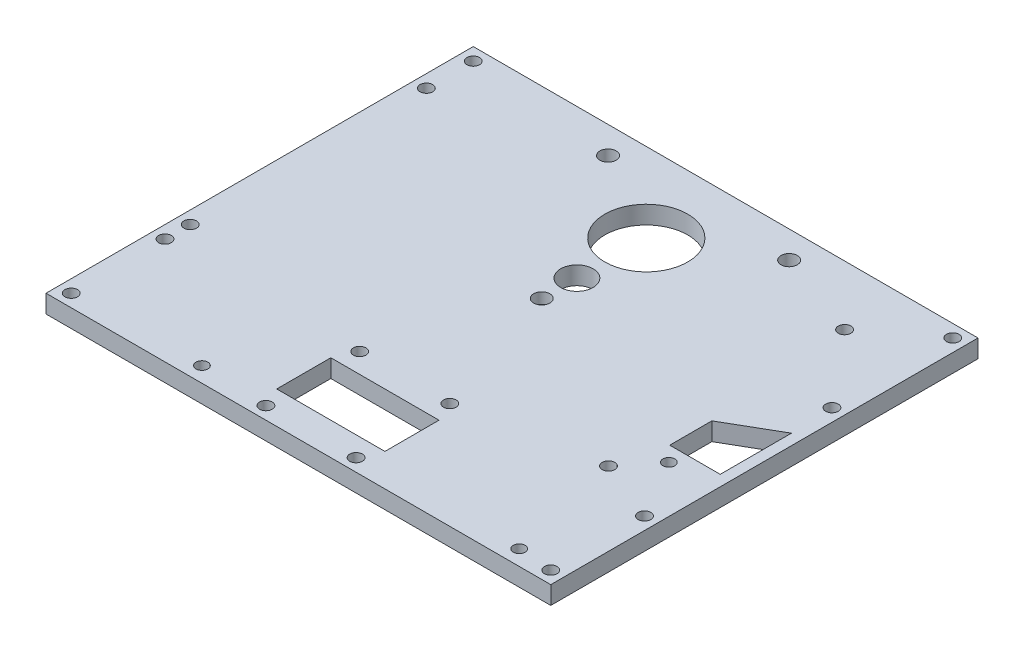
SolidWorks part; units mm, degrees
ref_plane "前视基准面" through (0, 0, 0) normal (0, 0, 1) x (1, 0, 0)
ref_plane "上视基准面" through (0, 0, 0) normal (0, 1, 0) x (1, 0, 0)
ref_plane "右视基准面" through (0, 0, 0) normal (1, 0, 0) x (0, 0, -1)
sketch "草图1" plane through (0, 0, 0) normal (0, 1, 0) x (1, 0, 0)
  line L1 (-40, 90) -> (40, 90)
  line L2 (-40, 90) -> (-40, -90)
  line L3 (-40, -90) -> (40, -90)
  line L4 (40, 90) -> (40, -90)
  line L5 (-40, 90) -> (40, -90) construction
  line L6 (-40, -90) -> (40, 90) construction
  point P0 (0, 0)
  dimension "D1" = 80
  dimension "D2" = 180
extrude "凸台-拉伸1" add sketch "草图1" along normal blind 5
sketch "草图5" plane through (0, 5, 0) normal (0, 1, 0) x (1, 0, 0)
  line L0 (40, -90) -> (40, 90) construction
  line L1 (-40, -90) -> (40, -90) construction
  line L2 (-40, -90) -> (-40, -10) construction
  line L3 (-40, -10) -> (40, -10) construction
  line L4 (40, -90) -> (40, -10) construction
  line L5 (-40, -10) -> (40, -90) construction
  line L6 (0, -50) -> (0, -79)
  line L7 (0, -50) -> (-25.1147, -35.5)
  line L8 (0, -50) -> (25.1147, -35.5)
  circle A0 centre (0, -50) radius 29
  circle A1 centre (0, -50) radius 19.25
  dimension "D2" = 58
  dimension "D5" = 38.5
  dimension "D1" = 80
  dimension "D3" = 120
  dimension "D4" = 120
sketch "草图6" plane through (0, 5, 0) normal (0, 1, 0) x (1, 0, 0)
  point P0 (0, -79)
  point P3 (25.1147, -35.5)
  point P6 (-25.1147, -35.5)
hole_wizard "孔2" positions "草图6" profile "草图7" legacy end condition through all
sketch "草图7" plane through (0, 5, 79) normal (1, 0, 0) x (0, 0, 1)
  line L0 (0, 0) -> (0, 5)
  line L1 (0, 5) -> (2.25, 5)
  line L2 (2.25, 5) -> (2.25, 0)
  line L3 (2.25, 0) -> (0, 0)
  line L4 (0, 110) -> (0, -10) construction
  dimension "直径" = 4.5
  dimension "深度" = 5
sketch "草图8" plane through (0, 5, 0) normal (0, 1, 0) x (1, 0, 0)
  point P0 (0, -50)
hole_wizard "孔3" positions "草图8" profile "草图9" legacy end condition through all
sketch "草图9" plane through (0, 5, 50) normal (1, 0, 0) x (0, 0, 1)
  line L0 (0, 0) -> (0, 5)
  line L1 (0, 5) -> (11.5, 5)
  line L2 (11.5, 5) -> (11.5, 0)
  line L3 (11.5, 0) -> (0, 0)
  line L4 (0, 110) -> (0, -10) construction
  dimension "直径" = 23
  dimension "深度" = 5
sketch "草图10" plane through (0, 5, 0) normal (0, 1, 0) x (1, 0, 0)
  line L0 (0, -50) -> (0, -79) construction
  circle A0 centre (0, -50) radius 19.25 construction
  point P0 (0, -69.25)
hole_wizard "孔4" positions "草图10" profile "草图11" legacy end condition through all
sketch "草图11" plane through (0, 5, 69.25) normal (1, 0, 0) x (0, 0, 1)
  line L0 (0, 0) -> (0, 5)
  line L1 (0, 5) -> (4.5, 5)
  line L2 (4.5, 5) -> (4.5, 0)
  line L3 (4.5, 0) -> (0, 0)
  line L4 (0, 110) -> (0, -10) construction
  dimension "直径" = 9
  dimension "深度" = 5
sketch "草图12" plane through (0, 5, 0) normal (0, 1, 0) x (1, 0, 0)
  line L0 (40, -90) -> (40, 90) construction
  line L1 (-40, -90) -> (40, -90)
  line L2 (-40, -90) -> (-40, -20)
  line L3 (-40, -20) -> (40, -20)
  line L4 (40, -90) -> (40, -20)
  line L6 (-40, -20) -> (40, -20)
  line L7 (-40, -20) -> (-40, 90)
  line L8 (-40, 90) -> (40, 90)
  line L9 (40, -20) -> (40, 90)
  line M7 (40, -90) -> (40, 90)
  line M8 (40, 90) -> (-40, 90)
  line M9 (-40, 90) -> (-40, -90)
  dimension "D1" = 70
extrude "切除-拉伸1" cut sketch "草图12" against normal blind 10 contours L3 M9 M7 M8
sketch "草图13" plane through (0, 5, 0) normal (0, 1, 0) x (1, 0, 0)
  line L1 (-40, -90) -> (40, -90)
  line L2 (-40, -90) -> (-40, -150)
  line L3 (-40, -150) -> (40, -150)
  line L4 (40, -90) -> (40, -150)
  dimension "D1" = 60
extrude "凸台-拉伸2" add sketch "草图13" against normal blind 5
sketch "草图14" plane through (0, 5, 0) normal (0, 1, 0) x (1, 0, 0)
  line L0 (-40, -150) -> (40, -150) construction
  line L1 (-40, -20) -> (-70, -20)
  line L2 (-40, -20) -> (-40, -150)
  line L3 (-40, -150) -> (-70, -150)
  line L4 (-70, -20) -> (-70, -150)
  line L5 (40, -20) -> (70, -20)
  line L6 (40, -20) -> (40, -150)
  line L7 (40, -150) -> (70, -150)
  line L8 (70, -20) -> (70, -150)
  dimension "D1" = 30
  dimension "D2" = 30
extrude "凸台-拉伸3" add sketch "草图14" against normal blind 5
sketch "草图15" plane through (0, 5, 0) normal (0, 1, 0) x (1, 0, 0)
  line L0 (70, -150) -> (70, -20) construction
  line L1 (-70, -20) -> (70, -20)
  line L2 (-70, -20) -> (-70, -28)
  line L3 (-70, -28) -> (70, -28)
  line L4 (70, -20) -> (70, -28)
  dimension "D1" = 8
extrude "切除-拉伸2" cut sketch "草图15" against normal blind 10
sketch "草图16" plane through (0, 5, 0) normal (0, 1, 0) x (1, 0, 0)
  line L0 (70, -150) -> (70, -28) construction
  line L1 (-70, -150) -> (70, -150)
  line L2 (-70, -150) -> (-70, -168)
  line L3 (-70, -168) -> (70, -168)
  line L4 (70, -150) -> (70, -168)
  dimension "D1" = 18
extrude "凸台-拉伸4" add sketch "草图16" against normal blind 5
sketch "草图18" plane through (0, 0, 0) normal (0, -1, 0) x (-1, 0, 0)
  point P0 (0, -79)
hole_wizard "孔5" positions "草图18" profile "草图19" legacy
sketch "草图19" plane through (0, 0, 79) normal (1, 0, 0) x (0, 0, -1)
  line L0 (0, 0) -> (0, 2)
  line L1 (0, 2) -> (4.5, 2)
  line L2 (4.5, 2) -> (4.5, 0)
  line L3 (4.5, 0) -> (0, 0)
  line L4 (0, 110) -> (0, -10) construction
  dimension "直径" = 9
  dimension "深度" = 2
sketch "草图20" plane through (0, 0, 0) normal (0, -1, 0) x (-1, 0, 0)
  line L0 (70, -113.5) -> (-70, -113.5)
  line L1 (70, -28) -> (70, -168) construction
  line L2 (-70, -168) -> (-70, -28) construction
  line L3 (70, -28) -> (-70, -28) construction
  line L4 (70, -41) -> (-70, -41)
  line L5 (70, -41) -> (-53, -113.5)
  line L6 (70, -113.5) -> (-70, -113.5)
  line L7 (70, -113.5) -> (70, -41)
  line L8 (70, -41) -> (-70, -41)
  line L9 (-70, -113.5) -> (-70, -41)
  line L10 (70, -113.5) -> (-53, -113.5)
  line L11 (70, -113.5) -> (70, -41)
  line L12 (70, -41) -> (-53, -41)
  line L13 (-53, -113.5) -> (-53, -41)
  line L15 (66.5, -110) -> (-49.5, -110)
  line L16 (66.5, -110) -> (66.5, -44.5)
  line L17 (66.5, -44.5) -> (-49.5, -44.5)
  line L18 (-49.5, -110) -> (-49.5, -44.5)
  line L19 (66.5, -110) -> (-49.5, -44.5) construction
  line L20 (66.5, -44.5) -> (-49.5, -110) construction
  point P12 (8.5, -77.25)
  dimension "D1" = 13
  dimension "D2" = 72.5
  dimension "D3" = 123
  dimension "D4" = 65.5
  dimension "D5" = 116
sketch "草图21" plane through (0, 0, 0) normal (0, -1, 0) x (-1, 0, 0)
  point P0 (-49.5, -44.5)
  point P3 (-49.5, -110)
  point P6 (66.5, -110)
  point P9 (66.5, -44.5)
hole_wizard "孔6" positions "草图21" profile "草图22" legacy end condition through all
sketch "草图22" plane through (49.5, 0, 44.5) normal (1, 0, 0) x (0, 0, -1)
  line L0 (0, 0) -> (0, 5)
  line L1 (0, 5) -> (1.75, 5)
  line L2 (1.75, 5) -> (1.75, 0)
  line L3 (1.75, 0) -> (0, 0)
  line L4 (0, 110) -> (0, -10) construction
  dimension "直径" = 3.5
  dimension "深度" = 5
sketch "草图23" plane through (0, 5, 0) normal (0, 1, 0) x (1, 0, 0)
  line L1 (-70, -113.5) -> (-9, -113.5)
  line L2 (-70, -113.5) -> (-70, -146.5)
  line L3 (-70, -146.5) -> (-9, -146.5)
  line L4 (-9, -113.5) -> (-9, -146.5)
  line L5 (-70, -113.5) -> (70, -113.5) construction
  line L6 (70, -146.5) -> (9, -146.5)
  line L7 (70, -146.5) -> (70, -113.5)
  line L8 (70, -113.5) -> (9, -113.5)
  line L9 (9, -146.5) -> (9, -113.5)
  point P14 (-66.5, -117)
  point P15 (-66.5, -143)
  point P16 (-12.5, -117)
  point P17 (-12.5, -143)
  dimension "D1" = 61
  dimension "D2" = 61
  dimension "D3" = 3.5
  dimension "D4" = 3.5
  dimension "D5" = 3.5
  dimension "D6" = 3.5
  dimension "D7" = 3.5
  dimension "D8" = 3.5
  dimension "D9" = 3.5
  dimension "D10" = 3.5
  dimension "D11" = 33
  dimension "D12" = 33
sketch "草图24" plane through (0, 5, 0) normal (0, 1, 0) x (1, 0, 0)
  point P0 (-66.5, -117)
  point P3 (-12.5, -117)
  point P6 (-12.5, -143)
  point P9 (-66.5, -143)
hole_wizard "孔7" positions "草图24" profile "草图25" legacy end condition through all
sketch "草图25" plane through (-66.5, 5, 117) normal (1, 0, 0) x (0, 0, 1)
  line L0 (0, 0) -> (0, 5)
  line L1 (0, 5) -> (1.75, 5)
  line L2 (1.75, 5) -> (1.75, 0)
  line L3 (1.75, 0) -> (0, 0)
  line L4 (0, 110) -> (0, -10) construction
  dimension "直径" = 3.5
  dimension "深度" = 5
ref_plane "基准面1" through (0, 0, 0) normal (-1, 0, 0) x (0, 0, 1)
mirror "镜向1" about plane through (0, 0, 0) normal (-1, 0, 0) of "孔7"
sketch "草图26" plane through (0, 5, 0) normal (0, 1, 0) x (1, 0, 0)
  line L1 (-70, -168) -> (70, -168)
  line L2 (-70, -168) -> (-70, -146.5)
  line L3 (-70, -146.5) -> (70, -146.5)
  line L4 (70, -168) -> (70, -146.5)
extrude "切除-拉伸3" cut sketch "草图26" against normal blind 10
sketch "草图27" plane through (0, 5, 0) normal (0, 1, 0) x (1, 0, 0)
  line L0 (-70, -28) -> (70, -28) construction
  line L1 (-70, -28) -> (-70, -146.5) construction
  line L2 (70, -146.5) -> (70, -28) construction
  point P0 (-66.5, -31.5)
  point P1 (66.5, -31.5)
  dimension "D1" = 3.5
  dimension "D2" = 3.5
  dimension "D3" = 3.5
  dimension "D4" = 3.5
sketch "草图28" plane through (0, 5, 0) normal (0, 1, 0) x (1, 0, 0)
  point P0 (-66.5, -31.5)
  point P3 (66.5, -31.5)
hole_wizard "孔8" positions "草图28" profile "草图29" legacy end condition through all
sketch "草图29" plane through (-66.5, 5, 31.5) normal (1, 0, 0) x (0, 0, 1)
  line L0 (0, 0) -> (0, 5)
  line L1 (0, 5) -> (1.75, 5)
  line L2 (1.75, 5) -> (1.75, 0)
  line L3 (1.75, 0) -> (0, 0)
  line L4 (0, 110) -> (0, -10) construction
  dimension "直径" = 3.5
  dimension "深度" = 5
sketch "草图30" plane through (0, 0, 0) normal (0, -1, 0) x (1, 0, 0)
  line L0 (0, 113.5) -> (0, 146.5)
  line L1 (-70, 113.5) -> (70, 113.5) construction
  line L2 (70, 146.5) -> (-70, 146.5) construction
  line L4 (-15, 122.5) -> (15, 122.5)
  line L5 (-15, 122.5) -> (-15, 137.5)
  line L6 (-15, 137.5) -> (15, 137.5)
  line L7 (15, 122.5) -> (15, 137.5)
  line L8 (-15, 122.5) -> (15, 137.5) construction
  line L9 (-15, 137.5) -> (15, 122.5) construction
  point P6 (0, 130)
  dimension "D1" = 30
  dimension "D2" = 15
extrude "切除-拉伸4" cut sketch "草图30" against normal through all contours L4 L7 L6 L0 | L6 L5 L4 L0
sketch "草图31" plane through (0, 0, 0) normal (0, -1, 0) x (1, 0, 0)
  line L0 (-70, 28) -> (70, 28) construction
  line L2 (70, 113.5) -> (70, 41) construction
  point P0 (66.5, 65)
  dimension "D1" = 37
  dimension "D2" = 3.5
sketch "草图32" plane through (0, 0, 0) normal (0, -1, 0) x (-1, 0, 0)
  point P0 (-66.5, -65)
hole_wizard "孔9" positions "草图32" profile "草图33" legacy end condition up to next
sketch "草图33" plane through (66.5, 0, 65) normal (1, 0, 0) x (0, 0, -1)
  line L0 (0, 0) -> (0, 5)
  line L1 (0, 5) -> (1.75, 5)
  line L2 (1.75, 5) -> (1.75, 0)
  line L3 (1.75, 0) -> (0, 0)
  line L4 (0, 110) -> (0, -10) construction
  dimension "直径" = 3.5
  dimension "深度" = 5
sketch "草图37" plane through (0, 0, 0) normal (0, -1, 0) x (-1, 0, 0)
  line L0 (-70, -113.5) -> (-70, -41) construction
  line L1 (-70, -103.5) -> (-53, -103.5)
  line L2 (-70, -103.5) -> (-70, -75)
  line L3 (-70, -75) -> (-53, -75)
  line L4 (-53, -103.5) -> (-53, -75)
  line L5 (-67, -103.5) -> (-67, -75)
  line L6 (-70, -146.5) -> (-9, -146.5) construction
  line L7 (70, -28) -> (-70, -28) construction
  line L8 (-70, -75) -> (-53, -84.815)
  line L9 (-70, -96.5) -> (-53, -96.5)
  dimension "D1" = 17
  dimension "D2" = 3
  dimension "D3" = 43
  dimension "D4" = 47
  dimension "D5" = 30
  dimension "D6" = 7
extrude "切除-拉伸5" cut sketch "草图37" against normal blind 10 contours L8 L5 L1 L4
sketch "草图38" plane through (0, 0, 0) normal (0, -1, 0) x (-1, 0, 0)
  line L0 (-70, -146.5) -> (-70, -113.5) construction
  line L1 (37, -146.5) -> (-63, -146.5)
  line L2 (37, -146.5) -> (37, -96.5)
  line L3 (37, -96.5) -> (-63, -96.5)
  line L4 (-63, -146.5) -> (-63, -96.5)
  line L6 (70, -146.5) -> (9, -146.5) construction
  line L8 (37, -96.5) -> (-63, -146.5)
  line L10 (-57, -100.75) -> (31, -100.75)
  line L11 (-57, -100.75) -> (-57, -142.25)
  line L12 (-57, -142.25) -> (31, -142.25)
  line L13 (31, -100.75) -> (31, -142.25)
  line L14 (-57, -100.75) -> (31, -142.25) construction
  line L15 (-57, -142.25) -> (31, -100.75) construction
  point P8 (-13, -121.5)
  dimension "D1" = 100
  dimension "D2" = 50
  dimension "D3" = 7
  dimension "D4" = 88
  dimension "D5" = 41.5
  dimension "D6" = 90
sketch "草图39" plane through (0, 0, 0) normal (0, -1, 0) x (-1, 0, 0)
  point P0 (-57, -100.75)
  point P3 (-57, -142.25)
  point P6 (31, -142.25)
hole_wizard "孔10" positions "草图39" profile "草图40" legacy end condition through all
sketch "草图40" plane through (57, 0, 100.75) normal (1, 0, 0) x (0, 0, -1)
  line L0 (0, 0) -> (0, 5)
  line L1 (0, 5) -> (1.65, 5)
  line L2 (1.65, 5) -> (1.65, 0)
  line L3 (1.65, 0) -> (0, 0)
  line L4 (0, 110) -> (0, -10) construction
  dimension "直径" = 3.3
  dimension "深度" = 5
